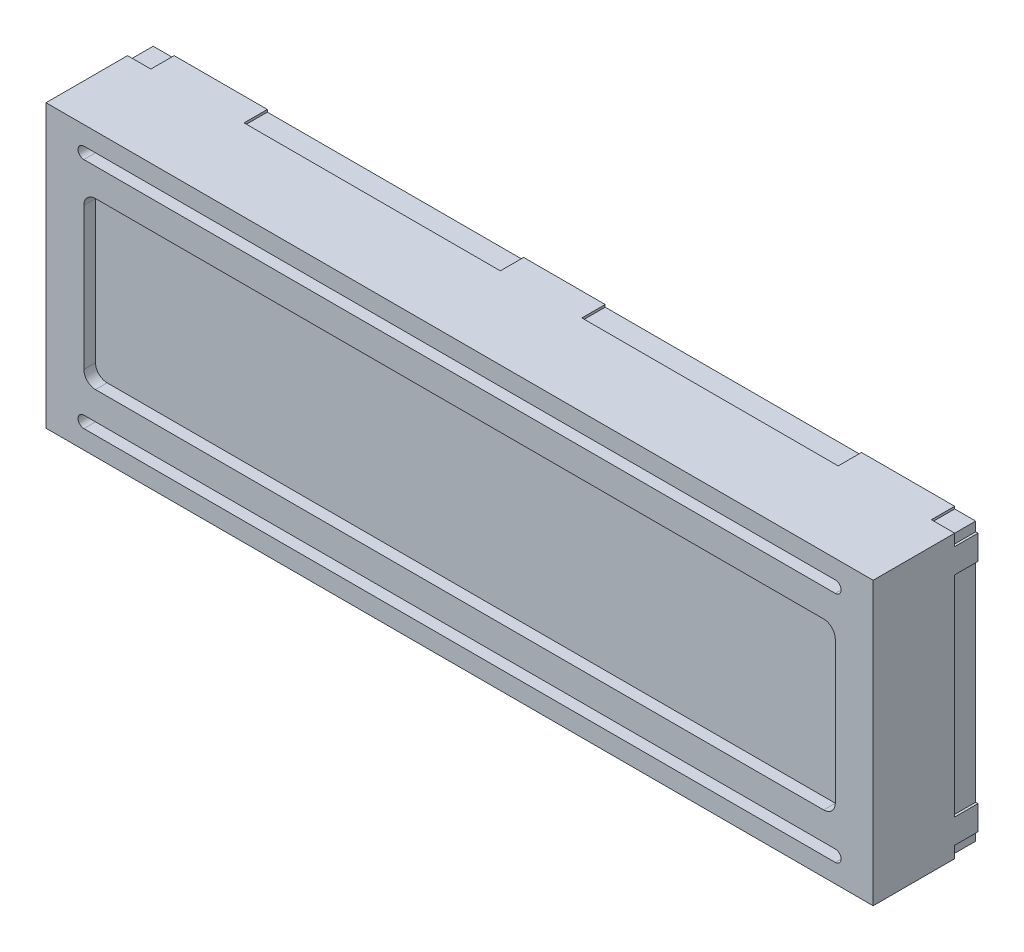
SolidWorks part; units mm, degrees
ref_plane "Plan de face" through (0, 0, 0) normal (0, 0, 1) x (1, 0, 0)
ref_plane "Plan de dessus" through (0, 0, 0) normal (0, 1, 0) x (1, 0, 0)
ref_plane "Plan de droite" through (0, 0, 0) normal (1, 0, 0) x (0, 0, -1)
sketch "Esquisse1" plane through (0, 0, 0) normal (0, 0, 1) x (1, 0, 0)
  line L0 (-43.4522, 0) -> (42.2721, 0) construction
  line L1 (-35.5, 12.1) -> (35.5, 12.1)
  line L2 (-35.5, 12.1) -> (-35.5, -12.1)
  line L3 (-35.5, -12.1) -> (35.5, -12.1)
  line L4 (35.5, 12.1) -> (35.5, -12.1)
  line L5 (0, -15.1886) -> (0, 13.5982) construction
  dimension "D1" = 71
  dimension "D2" = 24.2
extrude "Boss.-Extru.1" add sketch "Esquisse1" along normal blind 9
sketch "Esquisse2" plane through (0, 0, 9) normal (0, 0, 1) x (1, 0, 0)
  line L0 (-40.6999, 0) -> (38.4346, 0) construction
  line L1 (0, 15.5173) -> (0, -14.0826) construction
  line L3 (-31.25, 7.1) -> (31.25, 7.1)
  line L4 (-32.25, 6.1) -> (-32.25, -6.1)
  line L5 (-31.25, -7.1) -> (31.25, -7.1)
  line L6 (32.25, 6.1) -> (32.25, -6.1)
  arc A0 (31.25, 7.1) -> (32.25, 6.1) centre (31.25, 6.1) cw
  arc A1 (31.25, -7.1) -> (32.25, -6.1) centre (31.25, -6.1) ccw
  arc A2 (-32.25, -6.1) -> (-31.25, -7.1) centre (-31.25, -6.1) ccw
  arc A3 (-31.25, 7.1) -> (-32.25, 6.1) centre (-31.25, 6.1) ccw
  dimension "D3" = 1
  dimension "D1" = 64.5
  dimension "D2" = 14.2
extrude "Enlèv. mat.-Extru.1" cut sketch "Esquisse2" against normal blind 1
sketch "Esquisse3" plane through (0, 0, 9) normal (0, 0, 1) x (1, 0, 0)
  line L0 (-37.9132, 10) -> (38.4273, 10) construction
  line L1 (0, -15.0642) -> (0, 14.3091) construction
  line L2 (-32.25, 10) -> (32.25, 10) construction
  line L3 (-32.25, 10.5) -> (32.25, 10.5)
  line L4 (-32.25, 9.5) -> (32.25, 9.5)
  line L7 (-32.25, 6.1) -> (-32.25, -6.1) construction
  line L8 (-37.0017, 0) -> (36.9771, 0) construction
  line L9 (-32.25, -10) -> (32.25, -10) construction
  line L10 (-32.25, -10.5) -> (32.25, -10.5)
  line L11 (-32.25, -9.5) -> (32.25, -9.5)
  line L12 (-37.9132, -10) -> (38.4273, -10) construction
  arc A0 (-32.25, 10.5) -> (-32.25, 9.5) centre (-32.25, 10) ccw
  arc A1 (32.25, 9.5) -> (32.25, 10.5) centre (32.25, 10) ccw
  arc A2 (-32.25, -10.5) -> (-32.25, -9.5) centre (-32.25, -10) cw
  arc A3 (32.25, -9.5) -> (32.25, -10.5) centre (32.25, -10) cw
  point P7 (0, 10)
  point P19 (0, -10)
  dimension "D1" = 1
  dimension "D2" = 10
extrude "Enlèv. mat.-Extru.2" cut sketch "Esquisse3" against normal blind 1
sketch "Esquisse4" plane through (0, -12.1, 0) normal (0, -1, 0) x (1, 0, 0)
  line L0 (0, -5.3669) -> (0, 15.0474) construction
  line L1 (3.5, 2) -> (3.5, -2)
  line L2 (-25.5, 2) -> (-3.5, 2)
  line L3 (-25.5, 2) -> (-25.5, -2)
  line L4 (-25.5, -2) -> (-3.5, -2)
  line L5 (-3.5, 2) -> (-3.5, -2)
  line L6 (25.5, 2) -> (3.5, 2)
  line L7 (25.5, -2) -> (3.5, -2)
  line L8 (25.5, 2) -> (25.5, -2)
  line L9 (-35.5, 9) -> (-35.5, 0) construction
  line L10 (37.5, 2) -> (37.5, -2)
  line L11 (37.5, -2) -> (33.5, -2)
  line L12 (33.5, 2) -> (33.5, -2)
  line L13 (37.5, 2) -> (33.5, 2)
  line L14 (-37.5, 2) -> (-33.5, 2)
  line L15 (-37.5, 2) -> (-37.5, -2)
  line L16 (-37.5, -2) -> (-33.5, -2)
  line L17 (-33.5, 2) -> (-33.5, -2)
  dimension "D1" = 22
  dimension "D2" = 3.5
  dimension "D3" = 2
  dimension "D4" = 4
  dimension "D5" = 2
  dimension "D6" = 4
extrude "Enlèv. mat.-Extru.3" cut sketch "Esquisse4" against normal blind 0.2
mirror "Symétrie1" about plane through (0, 0, 0) normal (0, 1, 0) of "Enlèv. mat.-Extru.3"
sketch "Esquisse5" plane through (35.5, 0, 0) normal (1, 0, 0) x (0, 0, -1)
  line L0 (3.204, 0) -> (-10.87, 0) construction
  line L1 (-2, 12.1) -> (2, 12.1)
  line L2 (-2, 12.1) -> (-2, 11.1)
  line L3 (-2, 11.1) -> (2, 11.1)
  line L4 (2, 12.1) -> (2, 11.1)
  line L5 (0, -11.9) -> (0, 11.9) construction
  line L6 (-2, 9) -> (2, 9)
  line L7 (-2, 9) -> (-2, -9)
  line L8 (-2, -9) -> (2, -9)
  line L9 (2, 9) -> (2, -9)
  line L10 (2, -12.1) -> (2, -11.1)
  line L11 (-2, -12.1) -> (2, -12.1)
  line L12 (-2, -12.1) -> (-2, -11.1)
  line L13 (-2, -11.1) -> (2, -11.1)
  dimension "D1" = 2
  dimension "D2" = 4
  dimension "D3" = 1
  dimension "D4" = 18
extrude "Enlèv. mat.-Extru.4" cut sketch "Esquisse5" against normal blind 0.2
mirror "Symétrie2" about plane through (0, 0, 0) normal (1, 0, 0) of "Enlèv. mat.-Extru.4"
